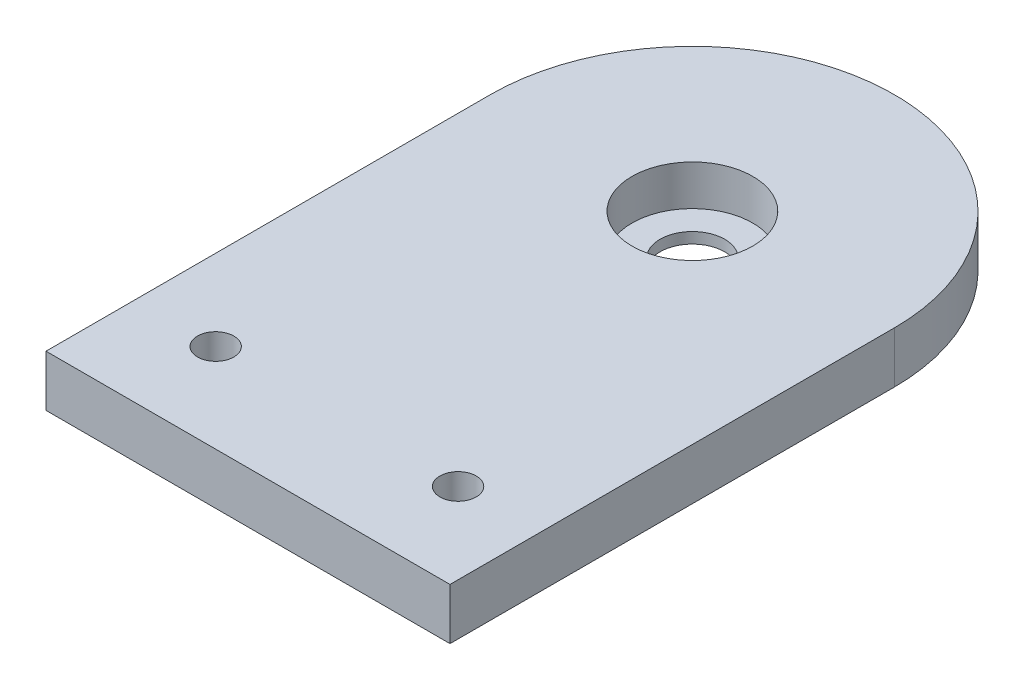
SolidWorks part; units mm, degrees
material "Aleación 6061"
ref_plane "Alzado" through (0, 0, 0) normal (0, 0, 1) x (1, 0, 0)
ref_plane "Planta" through (0, 0, 0) normal (0, 1, 0) x (1, 0, 0)
ref_plane "Vista lateral" through (0, 0, 0) normal (1, 0, 0) x (0, 0, -1)
sketch "Sk_Placa" plane through (0, 0, 0) normal (0, 1, 0) x (1, 0, 0)
  line L1 (-25, -526) -> (25, -526)
  line L2 (-25, -526) -> (-25, -490)
  line L3 (-25, -490) -> (25, -490)
  line L4 (25, -526) -> (25, -490)
  line L5 (-25, -526) -> (25, -490) construction
  line L6 (-25, -490) -> (25, -526) construction
  point P0 (0, -508)
  dimension "D1" = 50
  dimension "D2" = 36
  dimension "D3" = 508
extrude "Placa" add sketch "Sk_Placa" along normal blind 6.35 from offset 40.85
sketch "Sk_Extremo" plane through (0, 0, 0) normal (0, 1, 0) x (1, 0, 0)
  circle A0 centre (0, -490) radius 25
  dimension "D1" = 50
  dimension "D2" = 490
extrude "Extremo" add sketch "Sk_Extremo" along normal blind 6.35 from offset 40.85
sketch "Sk_Alojamiento_696ZZ" plane through (0, 0, 0) normal (0, 1, 0) x (1, 0, 0)
  circle A0 centre (0, -490) radius 7.475
  dimension "D1" = 14.95
  dimension "D2" = 490
extrude "Alojamiento_696ZZ" cut sketch "Sk_Alojamiento_696ZZ" along normal blind 5 from offset 39.5
sketch "Sk_Paso_extractor" plane through (0, 0, 0) normal (0, 1, 0) x (1, 0, 0)
  circle A0 centre (0, -490) radius 4
  dimension "D1" = 8
  dimension "D2" = 490
extrude "Paso_extractor" cut sketch "Sk_Paso_extractor" along normal blind 1.35 from offset 40.85
sketch "Sk_Extension_pestanas" plane through (0, 0, 0) normal (0, 1, 0) x (1, 0, 0)
  line L1 (-25, -545) -> (25, -545)
  line L2 (-25, -545) -> (-25, -526)
  line L3 (-25, -526) -> (25, -526)
  line L4 (25, -545) -> (25, -526)
  line L5 (-25, -545) -> (25, -526) construction
  line L6 (-25, -526) -> (25, -545) construction
  point P0 (0, -535.5)
  dimension "D1" = 50
  dimension "D2" = 19
  dimension "D3" = 535.5
extrude "Extension_pestanas" add sketch "Sk_Extension_pestanas" along normal blind 6.35 from offset 40.85
sketch "Sk_Pasantes_M4_repisa" plane through (0, 0, 0) normal (0, 1, 0) x (1, 0, 0)
  circle A0 centre (-15, -534) radius 2.25
  circle A1 centre (15, -534) radius 2.25
  dimension "D1" = 4.5
  dimension "D4" = 4.5
  dimension "D2" = 15
  dimension "D3" = 534
  dimension "D5" = 15
  dimension "D6" = 534
extrude "Pasantes_M4_repisa" cut sketch "Sk_Pasantes_M4_repisa" along normal blind 6.35 from offset 40.85
